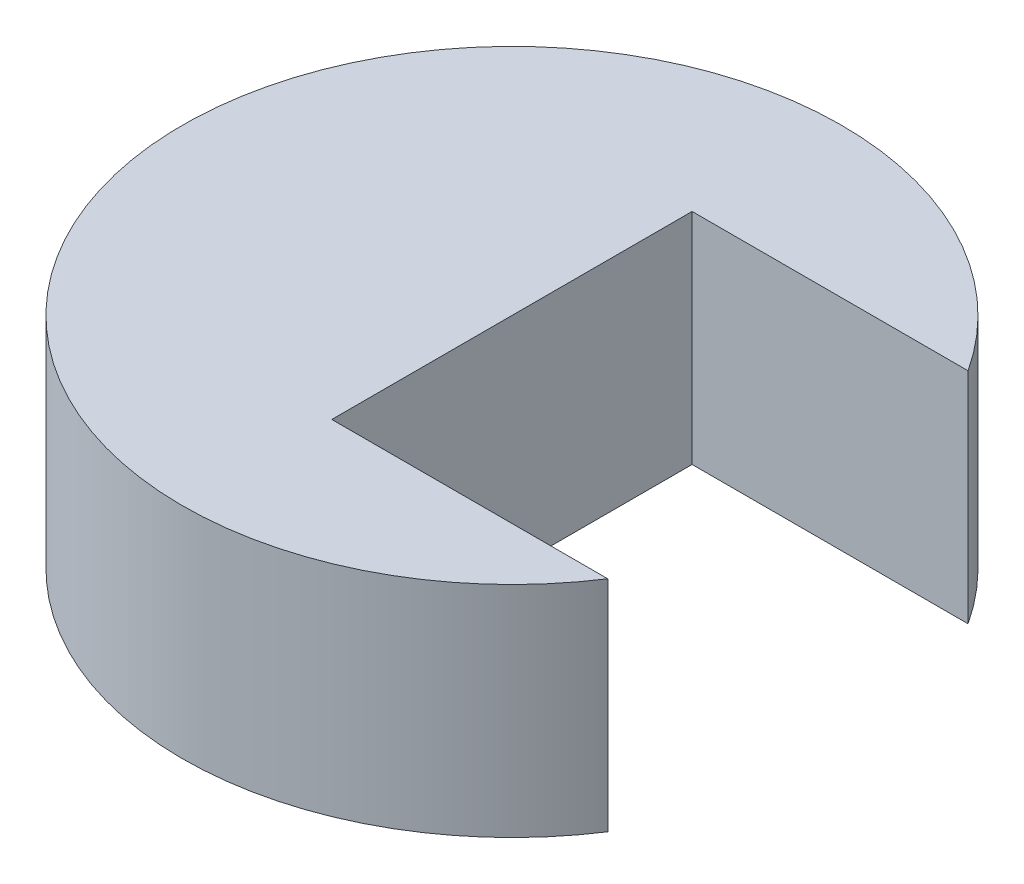
SolidWorks part; units mm, degrees
ref_plane "Front Plane" through (0, 0, 0) normal (0, 0, 1) x (1, 0, 0)
ref_plane "Top Plane" through (0, 0, 0) normal (0, 1, 0) x (1, 0, 0)
ref_plane "Right Plane" through (0, 0, 0) normal (1, 0, 0) x (0, 0, -1)
sketch "Sketch1" plane through (0, 0, 0) normal (0, 1, 0) x (1, 0, 0)
  line L1 (-21.0523, 0) -> (49.3226, 0)
  line L2 (-21.0523, 0) -> (-21.0523, 32.8817)
  line L3 (-21.0523, 32.8817) -> (49.3226, 32.8817)
  line L4 (49.3226, 0) -> (49.3226, 32.8817)
  circle A0 centre (-21.0523, 16.4409) radius 30.0747
extrude "Boss-Extrude1" add sketch "Sketch1" along normal blind 20 contours L3 A0 L1 L2
